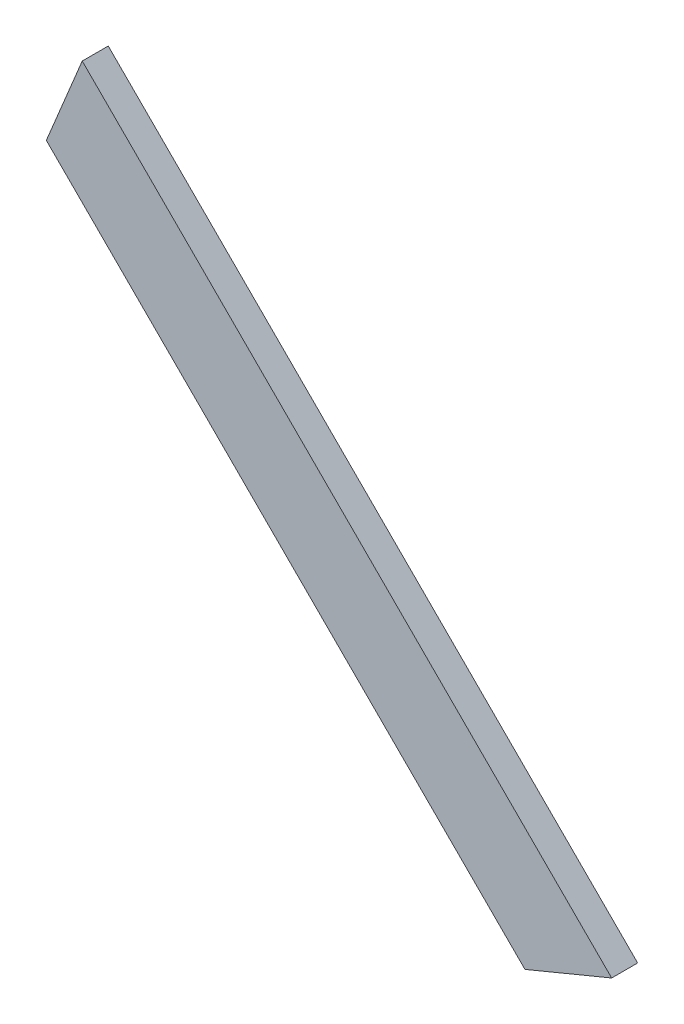
SolidWorks part; units mm, degrees
ref_plane "Front Plane" through (0, 0, 0) normal (0, 0, 1) x (1, 0, 0)
ref_plane "Top Plane" through (0, 0, 0) normal (0, 1, 0) x (1, 0, 0)
ref_plane "Right Plane" through (0, 0, 0) normal (1, 0, 0) x (0, 0, -1)
sketch "Sketch3" plane through (0, 0, 0) normal (0, 0, 1) x (1, 0, 0)
  line L0 (-528.0858, 1843.9468) -> (-140.2845, 1456.1455)
  line L1 (-528.0858, 1843.9468) -> (-554.3883, 1780.4468)
  line L2 (-140.2845, 1456.1455) -> (-203.7845, 1429.8429)
  line L3 (-554.3883, 1780.4468) -> (-203.7845, 1429.8429)
extrude "Boss-Extrude1" add sketch "Sketch3" along normal blind 19.05
